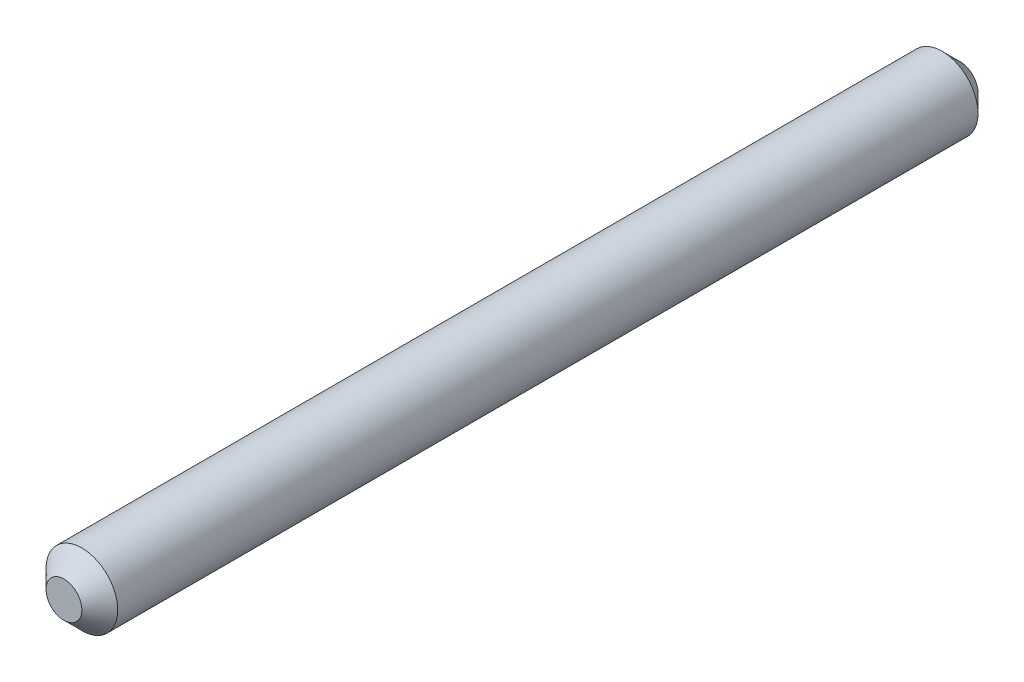
SolidWorks part; units mm, degrees
ref_plane "Front Plane" through (0, 0, 0) normal (0, 0, 1) x (1, 0, 0)
ref_plane "Top Plane" through (0, 0, 0) normal (0, 1, 0) x (1, 0, 0)
ref_plane "Right Plane" through (0, 0, 0) normal (1, 0, 0) x (0, 0, -1)
sketch "Sketch1" plane through (0, 0, 0) normal (0, 0, 1) x (1, 0, 0)
  circle A0 centre (0, 0) radius 1
  dimension "D1" = 2
extrude "Boss-Extrude1" add sketch "Sketch1" along normal blind 25
chamfer "Chamfer1" distance 0.5 angle 45 2 edges at (1, 0, 0) (1, 0, 25)
